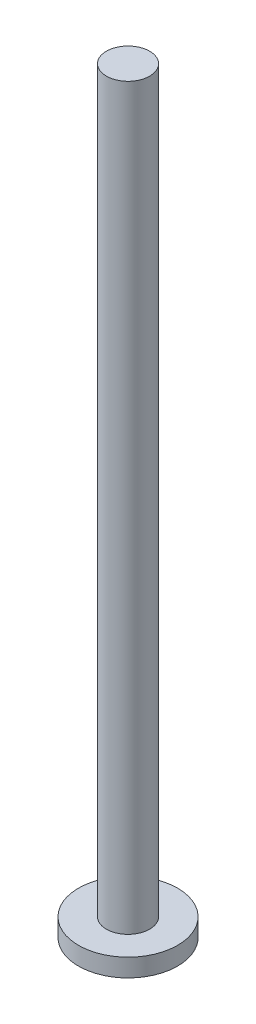
SolidWorks part; units mm, degrees
ref_plane "前视基准面" through (0, 0, 0) normal (0, 0, 1) x (1, 0, 0)
ref_plane "上视基准面" through (0, 0, 0) normal (0, 1, 0) x (1, 0, 0)
ref_plane "右视基准面" through (0, 0, 0) normal (1, 0, 0) x (0, 0, -1)
other "Configuration Table"
sketch "草图1" plane through (0, 0, 0) normal (0, 1, 0) x (1, 0, 0)
  circle A0 centre (0, 0) radius 2.4
  dimension "D1" = 4.8
extrude "凸台-拉伸1" add sketch "草图1" along normal blind 82
sketch "草图2" plane through (0, 0, 0) normal (0, -1, 0) x (1, 0, 0)
  circle A0 centre (0, 0) radius 5.5
  dimension "D1" = 11
extrude "凸台-拉伸2" add sketch "草图2" along normal blind 2
